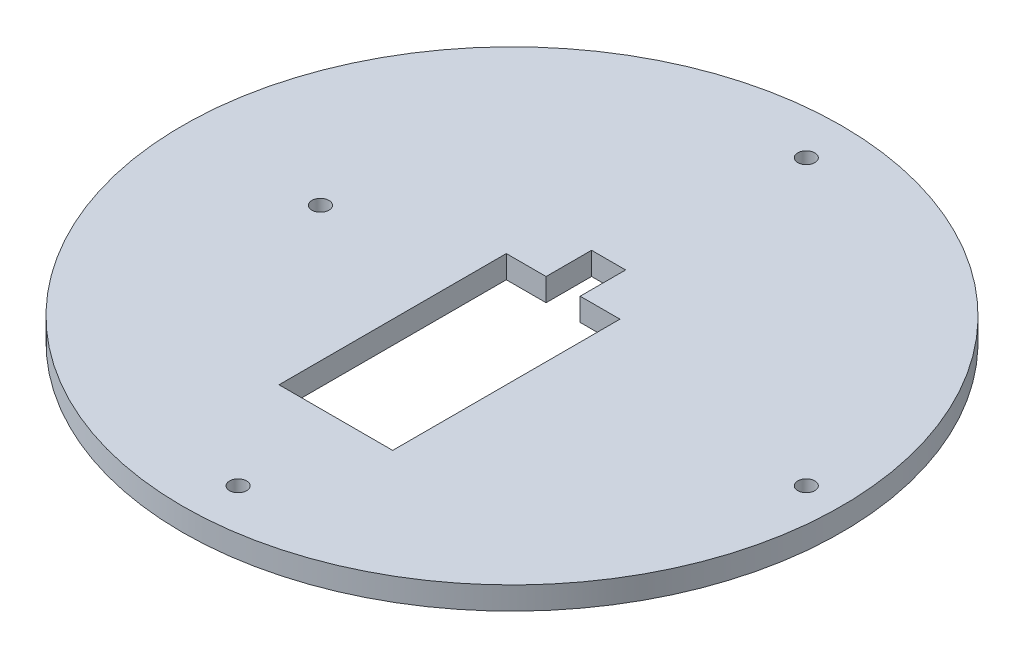
SolidWorks part; units mm, degrees
ref_plane "前视基准面" through (0, 0, 0) normal (0, 0, 1) x (1, 0, 0)
ref_plane "上视基准面" through (0, 0, 0) normal (0, 1, 0) x (1, 0, 0)
ref_plane "右视基准面" through (0, 0, 0) normal (1, 0, 0) x (0, 0, -1)
sketch "草图1" plane through (0, 0, 0) normal (0, 1, 0) x (1, 0, 0)
  circle A0 centre (0, 0) radius 58
  dimension "D1" = 116
extrude "凸台-拉伸1" add sketch "草图1" along normal blind 4
sketch "草图3" plane through (0, 0, 0) normal (0, -1, 0) x (1, 0, 0)
  circle A0 centre (1.7934, -50) radius 1.5
  circle A1 centre (-33.7066, 0) radius 1.5
  circle A2 centre (1.7934, 50) radius 1.5
  circle A3 centre (51.7934, 0) radius 1.5
extrude "切除-拉伸1" cut sketch "草图3" against normal blind 50
sketch "草图4" plane through (0, 4, 0) normal (0, 1, 0) x (1, 0, 0)
  line L0 (0, 81.3696) -> (0, -78.0747) construction
  line L1 (3, 9) -> (10, 9)
  line L2 (-10, -31) -> (10, -31)
  line L3 (-10, -31) -> (-10, 9)
  line L4 (-10, 9) -> (-3, 9)
  line L5 (10, -31) -> (10, 9)
  line L6 (-10, -31) -> (10, 9) construction
  line L7 (-10, 9) -> (10, -31) construction
  line L9 (-3, 9) -> (-3, 17)
  line L10 (-3, 17) -> (3, 17)
  line L11 (3, 9) -> (3, 17)
  line L12 (0, 9) -> (3, 17) construction
  line L13 (-3, 17) -> (0, 9) construction
  point P3 (0, -11)
  point P10 (0, 9)
  dimension "D1" = 20
  dimension "D2" = 40
  dimension "D5" = 6
  dimension "D6" = 8
extrude "切除-拉伸2" cut sketch "草图4" against normal blind 500
